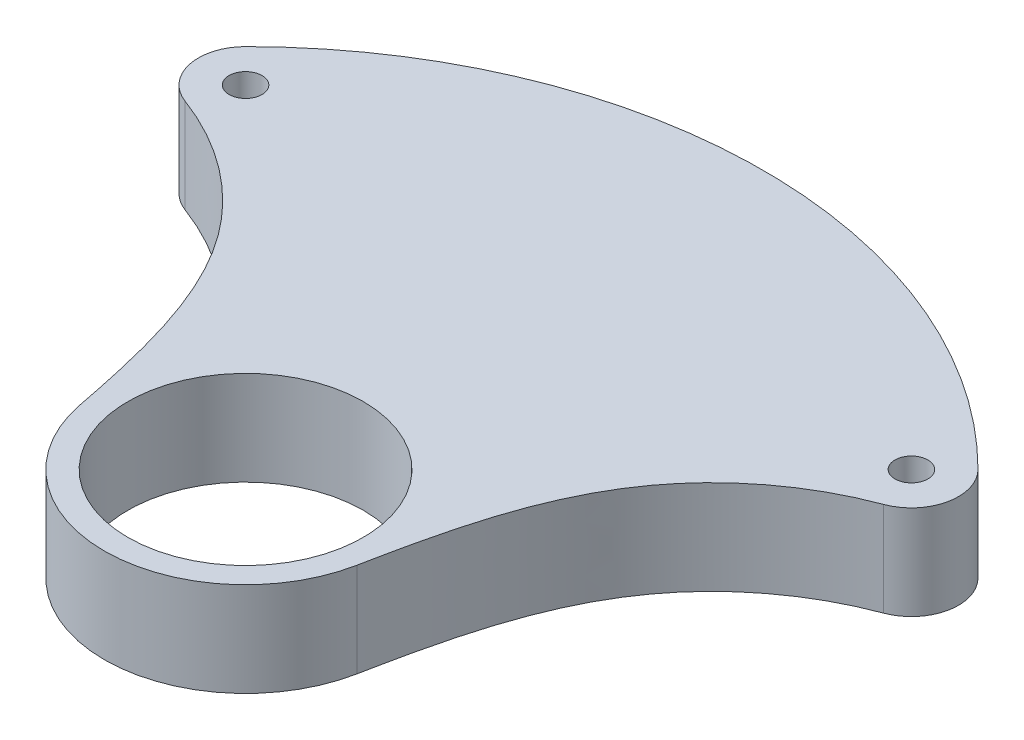
SolidWorks part; units mm, degrees
ref_plane "Front Plane" through (0, 0, 0) normal (0, 0, 1) x (1, 0, 0)
ref_plane "Top Plane" through (0, 0, 0) normal (0, 1, 0) x (1, 0, 0)
ref_plane "Right Plane" through (0, 0, 0) normal (1, 0, 0) x (0, 0, -1)
sketch "Sketch2" plane through (0, 0, 0) normal (0, 1, 0) x (1, 0, 0)
  line L0 (-31.8198, 31.8198) -> (-38.8909, 38.8909)
  line L1 (0, -55) -> (0, 55) construction
  line L2 (15, 0) -> (45, 0) construction
  circle A0 centre (0, 0) radius 45 construction
  circle A1 centre (0, 0) radius 55
  arc A2 (-38.8909, 38.8909) -> (-31.8198, 31.8198) centre (-35.3553, 35.3553) ccw
  arc A3 (38.8909, 38.8909) -> (31.8198, 31.8198) centre (35.3553, 35.3553) cw
  circle A4 centre (0, 0) radius 12.5
  circle A5 centre (0, 0) radius 15
  circle A6 centre (0, 0) radius 30 construction
  spline S0 degree 3 poles (-37.1013, 30.6701) (-31.1214, 28.4417) (-19.5397, 19.3543) (-16.3006, 5.1552) (-14.7183, -2.8935) knots 0 0 0 0 0.431745 1 1 1 1
  spline S1 degree 3 poles (37.1013, 30.6701) (31.1214, 28.4417) (19.5397, 19.3543) (16.3006, 5.1552) (14.7183, -2.8935) knots 0 0 0 0 0.431745 1 1 1 1
  point P23 (30, 0)
  dimension "D2" = 110
  dimension "D4" = 25
  dimension "D1" = 10
  dimension "D3" = 45
  dimension "D5" = 2.5
extrude "Boss-Extrude1" add sketch "Sketch2" along normal blind 10
sketch "Sketch3" plane through (0, 10, 0) normal (0, 1, 0) x (1, 0, 0)
  line L0 (0, 0) -> (-35.3553, 35.3553) construction
  line L1 (-35.3553, 35.3553) -> (35.3553, 35.3553) construction
  line L2 (35.3553, 35.3553) -> (0, 0) construction
  line L3 (0, -55) -> (0, 55) construction
  circle A0 centre (-35.3553, 35.3553) radius 1.75
  circle A1 centre (35.3553, 35.3553) radius 1.75
  dimension "D1" = 3.5
extrude "Cut-Extrude1" cut sketch "Sketch3" against normal up to next
equation "\"Width\"= 10mm"
equation "\"Thick\"= 10mm"
equation "\"Diameter\"= 110"
equation "\"D2@Sketch2\"= \"Diameter\""
equation "\"DegreeOfArc\"= 90deg"
equation "\"D3@Sketch2\"= \"DegreeOfArc\" / 2"
equation "\"D1@Boss-Extrude1\"= \"Thick\""
equation "\"D1@Sketch2\"= \"Width\""
equation "\"D4@Sketch2\"=25"
